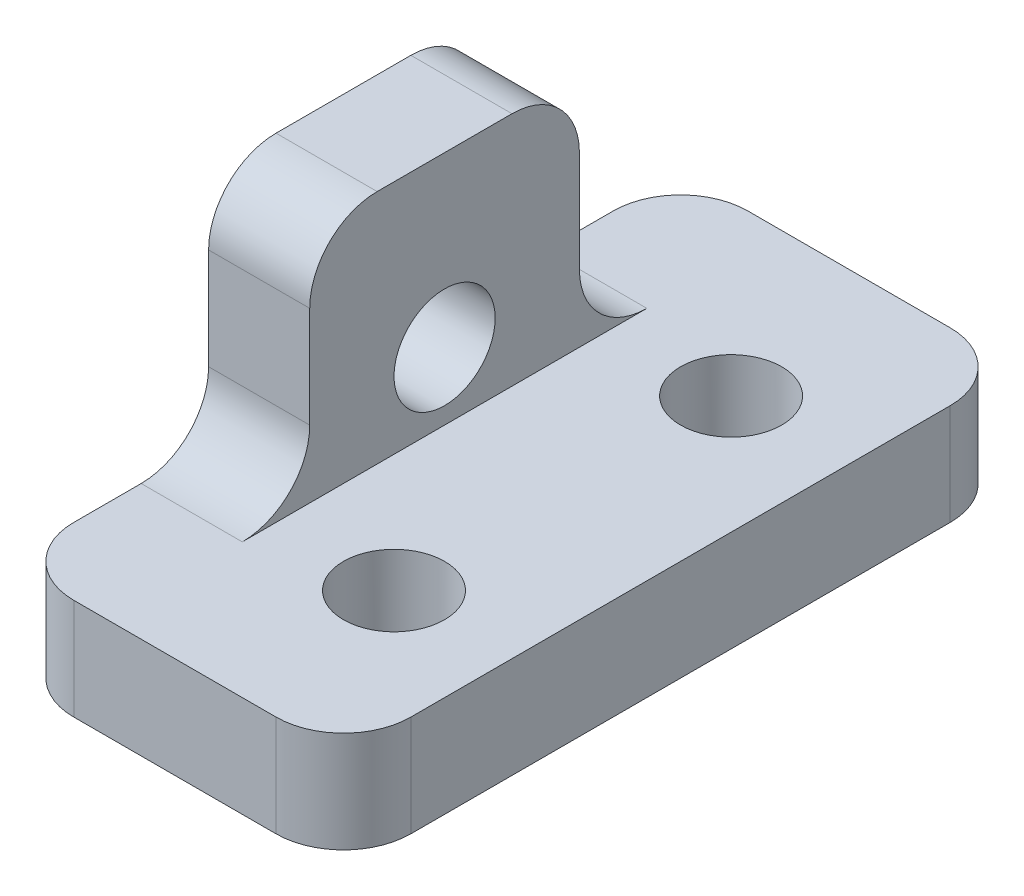
SolidWorks part; units mm, degrees
ref_plane "Front Plane" through (0, 0, 0) normal (0, 0, 1) x (1, 0, 0)
ref_plane "Top Plane" through (0, 0, 0) normal (0, 1, 0) x (1, 0, 0)
ref_plane "Right Plane" through (0, 0, 0) normal (1, 0, 0) x (0, 0, -1)
sketch "Sketch1" plane through (0, 0, 0) normal (1, 0, 0) x (0, 0, -1)
  line L0 (14, 10) -> (14, 3)
  line L1 (0, 0) -> (20, 0)
  line L2 (0, 0) -> (0, 3)
  line L3 (6, 10) -> (14, 10)
  line L4 (20, 0) -> (20, 3)
  line L5 (14, 3) -> (20, 3)
  line L6 (6, 10) -> (6, 3)
  line L7 (6, 3) -> (0, 3)
  circle A0 centre (10, 5) radius 1.5
  dimension "D1" = 3
  dimension "D2" = 5
  dimension "D5" = 10
  dimension "D3" = 10
  dimension "D4" = 20
  dimension "D6" = 6
  dimension "D7" = 6
  dimension "D8" = 7
extrude "Boss-Extrude1" add sketch "Sketch1" along normal blind 3
sketch "Sketch2" plane through (3, 0, 0) normal (1, 0, 0) x (0, 0, -1)
  line L1 (0, 0) -> (20, 0)
  line L2 (0, 0) -> (0, 3)
  line L3 (0, 3) -> (20, 3)
  line L4 (20, 0) -> (20, 3)
extrude "Boss-Extrude2" add sketch "Sketch2" along normal blind 7
sketch "Sketch3" plane through (0, 3, 0) normal (0, 1, 0) x (1, 0, 0)
  line L0 (0, 10) -> (3, 10) construction
  line L1 (0, 14) -> (0, 6) construction
  line L2 (3, 14) -> (3, 6) construction
  line L3 (0, 20) -> (0, 14) construction
  circle A0 centre (6.5, 15) radius 1.5
  circle A1 centre (6.5, 5) radius 1.5
  dimension "D1" = 3
  dimension "D3" = 6.5
  dimension "D2" = 5
extrude "Cut-Extrude1" cut sketch "Sketch3" against normal mid plane 25
fillet "Fillet1" radius 2 8 edges at (0, 1.5, -20) (1.5, 3, -14) (1.5, 3, -6) (0, 1.5, 0) (10, 1.5, -20) (1.5, 10, -14) (1.5, 10, -6) (10, 1.5, 0)
